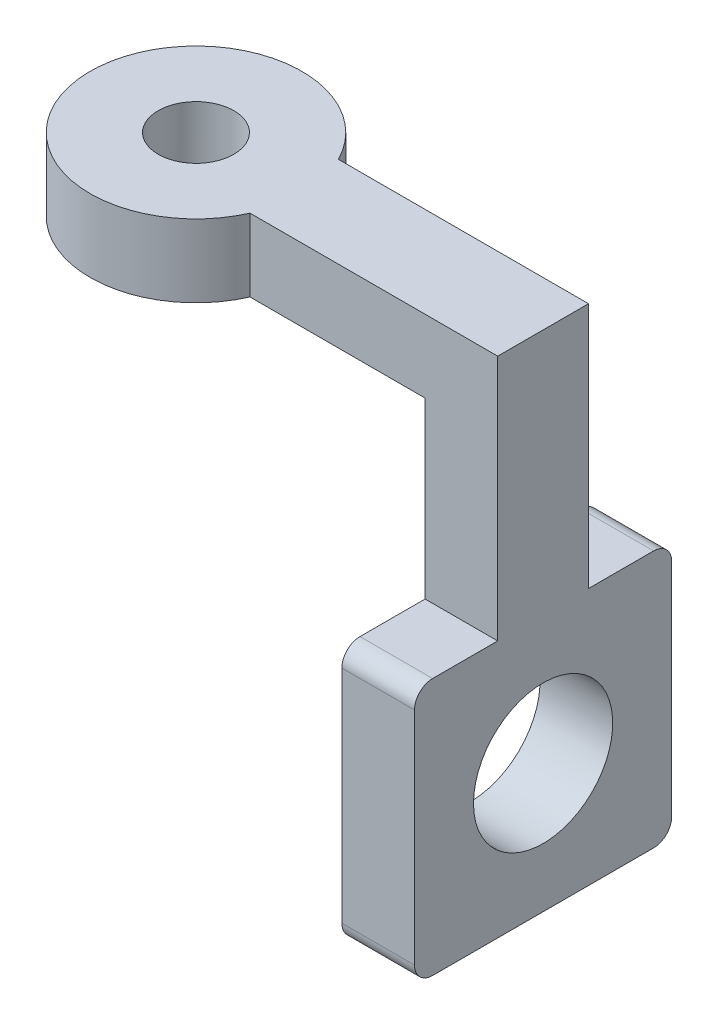
SolidWorks part; units mm, degrees
ref_plane "Ön Düzlem" through (0, 0, 0) normal (0, 0, 1) x (1, 0, 0)
ref_plane "Üst Düzlem" through (0, 0, 0) normal (0, 1, 0) x (1, 0, 0)
ref_plane "Sağ Düzlem" through (0, 0, 0) normal (1, 0, 0) x (0, 0, -1)
ref_plane "Düzlem1" through (0, 37.9375, 0) normal (0, -1, 0) x (1, 0, 0)
sketch "Çizim1" plane through (0, 37.9375, 0) normal (0, -1, 0) x (1, 0, 0)
  line L0 (-1.1534, 15) -> (-42.0763, 15)
  line L1 (-42.4753, 0) -> (-1.1534, 0)
  line L2 (-1.1534, 0) -> (-1.1534, 15)
  arc A0 (-42.0763, 15) -> (-42.4753, 0) centre (-58.0803, 7.9203) ccw
extrude "Yükseklik-Ekstrüzyon1" add sketch "Çizim1" against normal blind 12
sketch "Çizim2" plane through (0, 37.9375, 0) normal (0, -1, 0) x (1, 0, 0)
  line L0 (-13.1534, 0) -> (-13.1534, 15)
  line L1 (-13.1534, 15) -> (-1.1534, 15)
  line L2 (-1.1534, 15) -> (-1.1534, 0)
  line L3 (-1.1534, 0) -> (-13.1534, 0)
extrude "Yükseklik-Ekstrüzyon2" add sketch "Çizim2" along normal blind 71.25
sketch "Çizim3" plane through (0, 0, 0) normal (0, 0, -1) x (-1, 0, 0)
  line L0 (1.1534, -33.3125) -> (1.1534, 9.1875)
  line L1 (1.1534, 9.1875) -> (13.1534, 9.1875)
  line L2 (13.1534, 9.1875) -> (13.1534, -33.3125)
  line L3 (13.1534, -33.3125) -> (1.1534, -33.3125)
extrude "Yükseklik-Ekstrüzyon3" add sketch "Çizim3" along normal blind 13.75
sketch "Çizim4" plane through (0, 0, 15) normal (0, 0, 1) x (1, 0, 0)
  line L0 (-13.1534, -33.3125) -> (-13.1534, 9.1875)
  line L1 (-13.1534, 9.1875) -> (-1.1534, 9.1875)
  line L2 (-1.1534, 9.1875) -> (-1.1534, -33.3125)
  line L3 (-1.1534, -33.3125) -> (-13.1534, -33.3125)
extrude "Yükseklik-Ekstrüzyon4" add sketch "Çizim4" along normal blind 13.75
hole_wizard "Ø23.0 (23) Çap Delik1" positions "Çizim6" profile "Çizim5" hole size "Ø23.0" standard "ANSI Metric"
sketch "Çizim6" plane through (-13.1534, 0, 0) normal (-1, 0, 0) x (0, 0, 1)
  point P0 (7.5, -12.0625)
sketch "Çizim5" plane through (-13.1534, -12.0625, 7.5) normal (0, 1, 0) x (0, 0, 1)
  line L0 (0, 0) -> (0, 12)
  line L1 (0, 12) -> (11.5, 12)
  line L2 (11.5, 12) -> (11.5, 0)
  line L5 (11.5, 0) -> (0, 0)
  line L11 (0, -6.35) -> (0, 107.95) construction
  dimension "Thru Hole Dia." = 23
  dimension "Thru Hole Depth" = 12
hole_wizard "Ø12.5 (12.5) Çap Delik1" positions "Çizim8" profile "Çizim7" hole size "Ø12.5" standard "ANSI Metric"
sketch "Çizim8" plane through (0, 49.9375, 0) normal (0, 1, 0) x (1, 0, 0)
  point P0 (-58.0803, -7.9203)
sketch "Çizim7" plane through (-58.0803, 49.9375, 7.9203) normal (1, 0, 0) x (0, 0, 1)
  line L0 (0, 0) -> (0, 83.25)
  line L1 (0, 83.25) -> (6.25, 83.25)
  line L2 (6.25, 83.25) -> (6.25, 0)
  line L5 (6.25, 0) -> (0, 0)
  line L11 (0, -6.35) -> (0, 107.95) construction
  dimension "Thru Hole Dia." = 12.5
  dimension "Thru Hole Depth" = 83.25
fillet "Radyus1" radius 3 4 edges at (-7.1534, 9.1875, 28.75) (-7.1534, 9.1875, -13.75) (-7.1534, -33.3125, 28.75) (-7.1534, -33.3125, -13.75)
